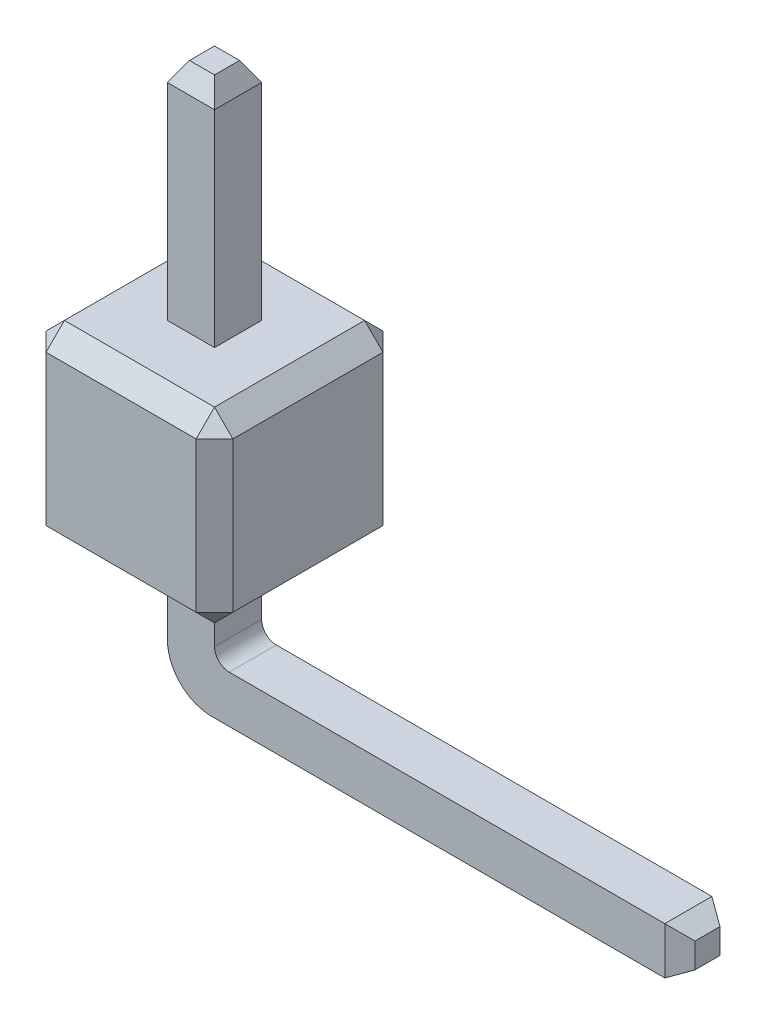
SolidWorks part; units mm, degrees
ref_plane "Plano frontal" through (0, 0, 0) normal (0, 0, 1) x (1, 0, 0)
ref_plane "Plano superior" through (0, 0, 0) normal (0, 1, 0) x (1, 0, 0)
ref_plane "Plano direito" through (0, 0, 0) normal (1, 0, 0) x (0, 0, -1)
sketch "Esboço1" plane through (0, 0, 0) normal (0, 0, 1) x (1, 0, 0)
  line L0 (0.32, 0.2) -> (-0.32, 0.2)
  line L1 (-0.32, 5.8) -> (0.32, 5.8)
  line L2 (-0.32, 5.8) -> (-0.32, 0.2)
  line L4 (0.32, 5.8) -> (0.32, 0.2)
  line L5 (-0.32, 5.8) -> (0, 0) construction
  line L6 (0, 0) -> (0.32, 5.8) construction
  point P0 (0, 0)
  dimension "D1" = 0.64
  dimension "D2" = 5.6
  dimension "D3" = 5.8
  dimension "D4" = 0.32
extrude "Ressalto-extrusão1" add sketch "Esboço1" along normal mid plane 0.64
sketch "Esboço2" plane through (0, 0, 0) normal (0, 0, 1) x (1, 0, 0)
  line L0 (0.32, 5.8) -> (-0.32, 5.8) construction
  line L1 (1.27, 2.74) -> (-1.27, 2.74)
  line L2 (1.27, 2.74) -> (1.27, 0.2)
  line L3 (1.27, 0.2) -> (-1.27, 0.2)
  line L4 (-1.27, 2.74) -> (-1.27, 0.2)
  line L5 (1.27, 2.74) -> (-1.27, 0.2) construction
  line L6 (1.27, 0.2) -> (-1.27, 2.74) construction
  line L7 (0, 0) -> (0, 5.8) construction
  point P0 (0, 1.47)
  dimension "D1" = 3.06
  dimension "D2" = 2.54
  dimension "D3" = 2.54
extrude "Ressalto-extrusão2" add sketch "Esboço2" along normal mid plane 2.54
sketch "Esboço3" plane through (0, 0, 0) normal (0, 0, 1) x (1, 0, 0)
  line L0 (0, 0.2) -> (0, -1.3) construction
  line L2 (-1.27, 0.2) -> (1.27, 0.2) construction
  line L3 (0, -1.3) -> (6.7, -1.3) construction
  line L8 (0.32, 0.2) -> (-0.32, 0.2)
  line L9 (-0.32, 0.2) -> (-0.32, -1.62)
  line L14 (-0.32, -1.62) -> (6.7, -1.62)
  line L15 (6.7, -0.98) -> (6.7, -1.62)
  line L16 (0.32, -0.98) -> (6.7, -0.98)
  line L17 (0.32, 0.2) -> (0.32, -0.98)
  point P11 (0.32, -2.48)
  point P12 (6, -2.48)
  point P14 (0, 0)
  dimension "D1" = 1.5
  dimension "D2" = 6.7
  dimension "D3" = 0.64
  dimension "D4" = 0.32
extrude "Ressalto-extrusão3" add sketch "Esboço3" along normal mid plane 0.64 contours L9 L14 L15 L16 L17 L8
fillet "Filete1" radius 0.2 1 edges at (0.32, -0.98, 0)
fillet "Filete2" radius 0.6 1 edges at (-0.32, -1.62, 0)
chamfer "Chanfro1" distance 0.15 distance2 0.26 4 edges at (0, 5.8, -0.32) (0.32, 5.8, 0) (0, 5.8, 0.32) (-0.32, 5.8, 0)
chamfer "Chanfro2" distance 0.26 distance2 0.15 4 edges at (6.7, -1.3, -0.32) (6.7, -0.98, 0) (6.7, -1.3, 0.32) (6.7, -1.62, 0)
chamfer "Chanfro3" distance 0.25 angle 45 12 edges at (-1.27, 2.74, 0) (0, 2.74, 1.27) (1.27, 2.74, 0) (0, 2.74, -1.27) (1.27, 0.2, 0) (1.27, 1.47, 1.27) (0, 0.2, 1.27) (-1.27, 1.47, 1.27) (-1.27, 0.2, 0) (1.27, 1.47, -1.27) (0, 0.2, -1.27) (-1.27, 1.47, -1.27)
